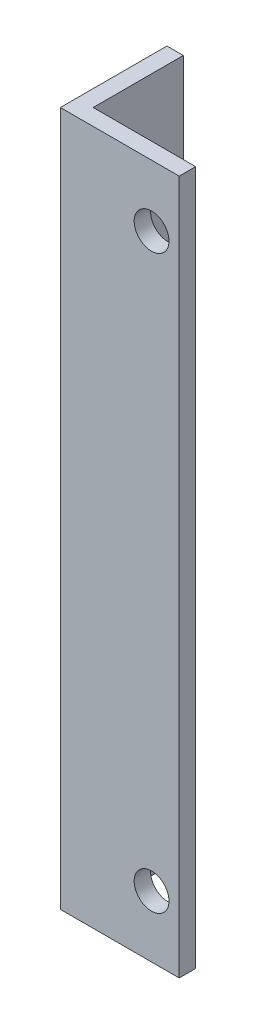
SolidWorks part; units mm, degrees
ref_plane "Alzado" through (0, 0, 0) normal (0, 0, 1) x (1, 0, 0)
ref_plane "Planta" through (0, 0, 0) normal (0, 1, 0) x (1, 0, 0)
ref_plane "Vista lateral" through (0, 0, 0) normal (1, 0, 0) x (0, 0, -1)
sketch "Croquis1" plane through (0, 0, 0) normal (0, 1, 0) x (1, 0, 0)
  line L0 (0, 0) -> (25, 0)
  line L1 (25, 0) -> (25, -3)
  line L2 (25, -3) -> (0, -3)
  line L3 (0, -3) -> (0, 0)
extrude "Saliente-Extruir1" add sketch "Croquis1" along normal blind 195
sketch "Croquis2" plane through (0, 0, 3) normal (0, 0, 1) x (1, 0, 0)
  line L0 (0, 195) -> (0, 0) construction
  line L1 (0, 0) -> (25, 0) construction
  line L2 (0, 195) -> (25, 195) construction
  circle A0 centre (18.25, 180) radius 4.25
  circle A1 centre (18.25, 97.5) radius 4.25
  circle A2 centre (18.25, 15) radius 4.25
  dimension "D1" = 18.25
  dimension "D2" = 15
  dimension "D3" = 97.5
  dimension "D4" = 15
extrude "Cortar-Extruir1" cut sketch "Croquis2" against normal blind 195
sketch "Croquis3" plane through (0, 195, 0) normal (0, 1, 0) x (1, 0, 0)
  line L1 (0, -3) -> (-4, -3)
  line L2 (0, -3) -> (0, 22)
  line L3 (0, 22) -> (-4, 22)
  line L4 (-4, -3) -> (-4, 22)
  dimension "D1" = 4
extrude "Saliente-Extruir2" add sketch "Croquis3" against normal blind 195
sketch "Croquis4" plane through (0, 0, 3) normal (0, 0, 1) x (1, 0, 0)
  line L1 (25, 195) -> (-4, 195)
  line L2 (25, 195) -> (25, 0)
  line L3 (25, 0) -> (-4, 0)
  line L4 (-4, 195) -> (-4, 0)
  circle A0 centre (18.25, 15) radius 4.25
  circle A1 centre (18.25, 97.5) radius 4.25
  circle A2 centre (18.25, 180) radius 4.25
extrude "Saliente-Extruir3" add sketch "Croquis4" along normal blind 1
sketch "Croquis5" plane through (0, 0, 4) normal (0, 0, 1) x (1, 0, 0)
  line L0 (-4, 0) -> (25, 0) construction
  line L1 (25, 195) -> (-55.6688, 195)
  line L2 (25, 195) -> (25, 169.5)
  line L3 (25, 169.5) -> (-55.6688, 169.5)
  line L4 (-55.6688, 195) -> (-55.6688, 169.5)
  dimension "D1" = 169.5
extrude "Cortar-Extruir2" cut sketch "Croquis5" against normal blind 30
sketch "Croquis6" plane through (0, 0, 4) normal (0, 0, 1) x (1, 0, 0)
  line L0 (25, 169.5) -> (-4, 169.5) construction
  circle A0 centre (18.25, 154.5) radius 4.25
  circle A1 centre (18.25, 97.5) radius 4.25 construction
  dimension "D1" = 0
  dimension "D2" = 15
extrude "Cortar-Extruir3" cut sketch "Croquis6" against normal blind 30
sketch "Croquis7" plane through (0, 0, 4) normal (0, 0, 1) x (1, 0, 0)
  circle A0 centre (18.25, 97.5) radius 4.25
extrude "Saliente-Extruir4" add sketch "Croquis7" against normal blind 4
